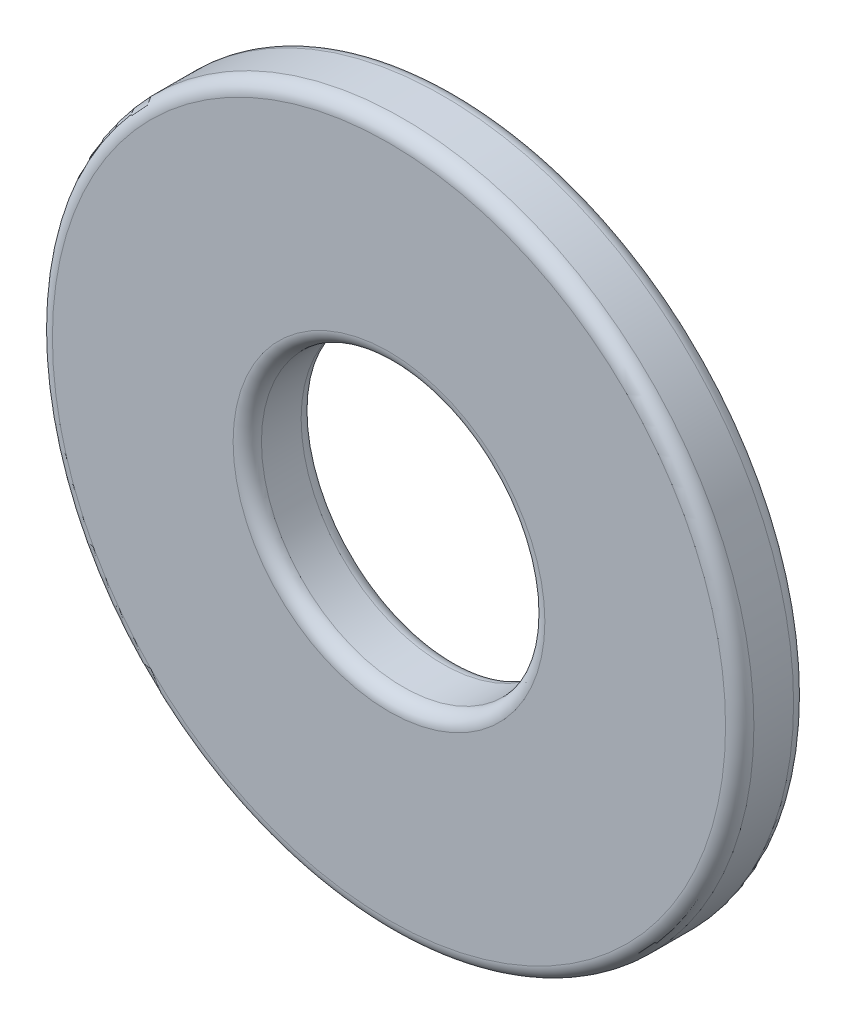
SolidWorks part; units mm, degrees
ref_plane "Plano frontal" through (0, 0, 0) normal (0, 0, 1) x (1, 0, 0)
ref_plane "Plano superior" through (0, 0, 0) normal (0, 1, 0) x (1, 0, 0)
ref_plane "Plano direito" through (0, 0, 0) normal (1, 0, 0) x (0, 0, -1)
sketch "Esboço1" plane through (0, 0, 0) normal (0, 0, 1) x (1, 0, 0)
  circle A0 centre (0, 0) radius 2
  circle A1 centre (0, 0) radius 4.95
  dimension "D1" = 4
  dimension "D2" = 9.9
extrude "Ressalto-extrusão1" add sketch "Esboço1" along normal blind 0.96
fillet "Filete1" radius 0.2 4 edges at (2, 0, 0) (4.95, 0, 0) (2, 0, 0.96) (4.95, 0, 0.96)
